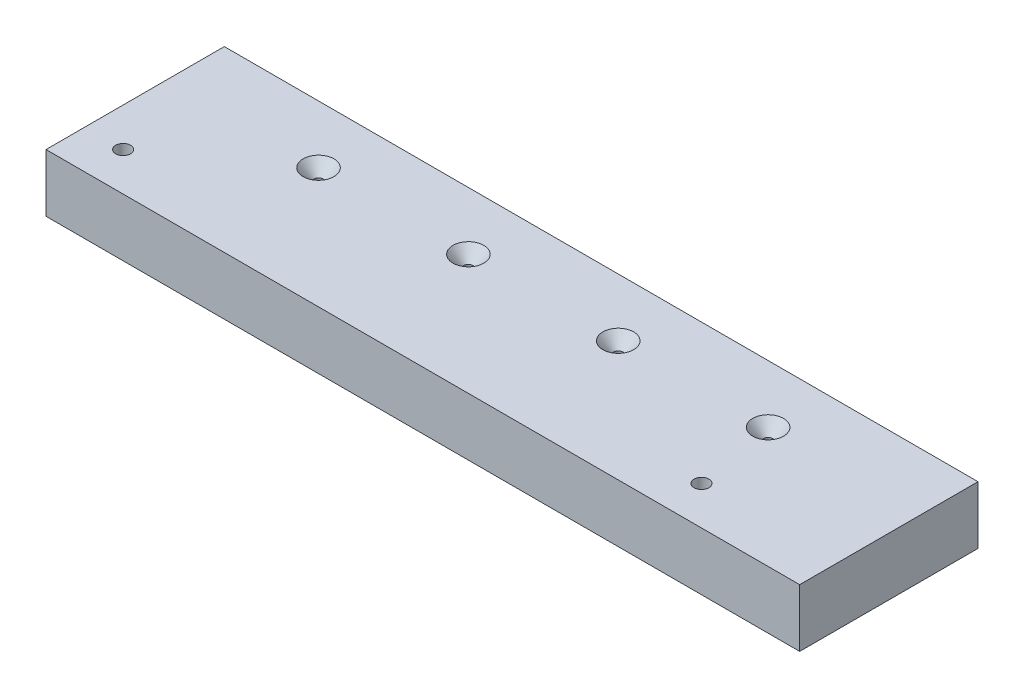
SolidWorks part; units mm, degrees
material "Beech"
ref_plane "Front Plane" through (0, 0, 0) normal (0, 0, 1) x (1, 0, 0)
ref_plane "Top Plane" through (0, 0, 0) normal (0, 1, 0) x (1, 0, 0)
ref_plane "Right Plane" through (0, 0, 0) normal (1, 0, 0) x (0, 0, -1)
sketch "Sketch1" plane through (0, 0, 0) normal (0, 0, 1) x (1, 0, 0)
  line L0 (248.25, 82.8417) -> (248.25, -188.5238) construction
  line L1 (248.25, 38.1) -> (0, 38.1)
  line L2 (248.25, 38.1) -> (248.25, 57.15)
  line L3 (248.25, 57.15) -> (0, 57.15)
  line L4 (0, 38.1) -> (0, 57.15)
  line L5 (-12.7, 38.1) -> (267.3, 38.1) construction
  line L6 (0, 82.8417) -> (0, -188.5238) construction
  dimension "D1" = 19.05
extrude "Boss-Extrude1" add sketch "Sketch1" along normal blind 38.1
hole_wizard "Hole1" positions "Sketch2" profile "Sketch3" legacy
sketch "Sketch2" plane through (-1090.5128, -52.975, -12.7) normal (0, 0, -1) x (0, 1, 0)
  line L0 (100.6, 1338.7628) -> (100.6, 1090.5128) construction
  line L6 (0.134, 1338.7628) -> (0.134, 1090.5128) construction
  point P12 (100.6, 1313.3628)
  point P14 (100.6, 1115.9128)
  point P16 (100.6, 1214.6378)
  point P22 (-100.332, 1214.6378)
  point P23 (-100.332, 1115.9128)
  point P24 (-100.332, 1313.3628)
sketch "Sketch3" plane through (222.85, -153.307, -12.7) normal (1, 0, 0) x (0, 1, 0)
  line L0 (0, 0) -> (0, 32.7039)
  line L1 (0, 32.7039) -> (1.5875, 31.75)
  line L2 (1.5875, 31.75) -> (1.5875, 4.0177)
  line L3 (1.5875, 4.0177) -> (5.08, 0)
  line L4 (5.08, 0) -> (0, 0)
  line L5 (0, -14.3089) -> (0, 102.4216) construction
  line L6 (0, 32.7039) -> (-1.5875, 31.75) construction
  line L7 (-1.5875, 4.0177) -> (-5.08, 0) construction
  dimension "Diameter" = 3.175
  dimension "Depth" = 31.75
  dimension "C-Sink Diameter" = 10.16
  dimension "C-Sink Angle" = 82
  dimension "Drill Angle" = 118
hole_wizard "Hole2" positions "Sketch4" profile "Sketch5" legacy
sketch "Sketch4" plane through (-1090.5128, 57.15, -415.7924) normal (0, 1, 0) x (0.3746, 0, 0.9272)
  line L0 (904.6882, 1078.3844) -> (811.6921, 848.211) construction
  line L4 (858.1902, 963.2977) -> (876.6817, 1009.0658)
  line L5 (876.6817, 1009.0658) -> (895.1732, 1054.8339)
  line L7 (858.1902, 963.2977) -> (875.853, 956.1614) construction
  point P20 (885.9274, 1031.9499)
  point P22 (867.4359, 986.1818)
  point P25 (830.4529, 894.6455)
  point P26 (848.9444, 940.4136)
sketch "Sketch5" plane through (99.4437, 57.15, 19.05) normal (1, 0, 0) x (0, 0, 1)
  line L0 (0, 0) -> (0, 58.1039)
  line L1 (0, 58.1039) -> (1.5875, 57.15)
  line L2 (1.5875, 57.15) -> (1.5875, 4.0177)
  line L3 (1.5875, 4.0177) -> (5.08, 0)
  line L4 (5.08, 0) -> (0, 0)
  line L5 (0, -14.3089) -> (0, 102.4216) construction
  line L6 (0, 58.1039) -> (-1.5875, 57.15) construction
  line L7 (-1.5875, 4.0177) -> (-5.08, 0) construction
  dimension "Diameter" = 3.175
  dimension "Depth" = 57.15
  dimension "C-Sink Diameter" = 10.16
  dimension "C-Sink Angle" = 82
  dimension "Drill Angle" = 118
sketch "Sketch6" plane through (0, 57.15, 0) normal (0, 1, 0) x (1, 0, 0)
  line L0 (248.25, -38.1) -> (248.25, 0) construction
  line L1 (0, -38.1) -> (248.25, -38.1)
  line L2 (0, -38.1) -> (0, -58.7379)
  line L3 (0, -58.7379) -> (248.25, -58.7379)
  line L4 (248.25, -38.1) -> (248.25, -58.7379)
  point P7 (0, -58.7379)
  dimension "D1" = 20.6379
extrude "Boss-Extrude3" add sketch "Sketch6" against normal up to vertex (19.05 mm away) up to point (248.25, 38.1, 38.1)
hole_wizard "#8 Clearance Hole1" positions "Sketch7" profile "Sketch8" hole size "#8" standard "ANSI Inch" end condition up to next
sketch "Sketch7" plane through (0, 57.15, 0) normal (0, 1, 0) x (1, 0, 0)
  point P0 (12.7, -46.0379)
  point P2 (203.2, -46.0379)
sketch "Sketch8" plane through (12.7, 57.15, 46.0379) normal (1, 0, 0) x (0, 0, 1)
  line L0 (0, 0) -> (0, 19.05)
  line L1 (0, 19.05) -> (2.4574, 19.05)
  line L2 (2.4574, 19.05) -> (2.4574, 0)
  line L5 (2.4574, 0) -> (0, 0)
  line L11 (0, -6.35) -> (0, 107.95) construction
  dimension "Thru Hole Dia." = 4.9149
  dimension "Thru Hole Depth" = 19.05
